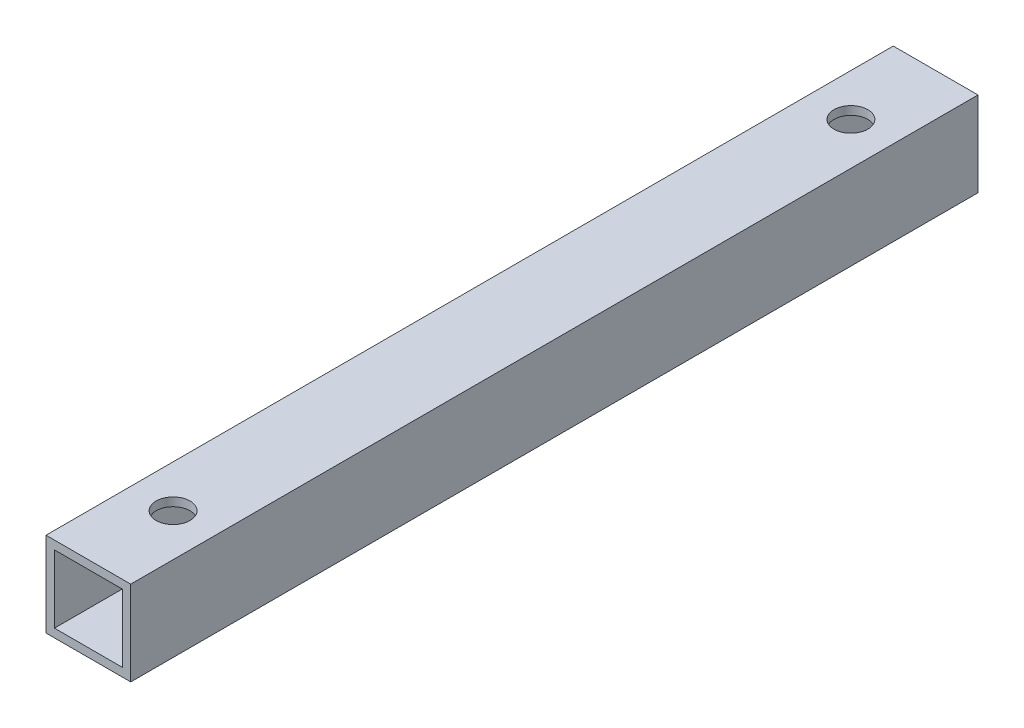
SolidWorks part; units mm, degrees
ref_plane "前视基准面" through (0, 0, 0) normal (0, 0, 1) x (1, 0, 0)
ref_plane "上视基准面" through (0, 0, 0) normal (0, 1, 0) x (1, 0, 0)
ref_plane "右视基准面" through (0, 0, 0) normal (1, 0, 0) x (0, 0, -1)
sketch "草图1" plane through (0, 0, 0) normal (0, 0, 1) x (1, 0, 0)
  line L0 (0, 0) -> (0, 8)
  line L1 (0, 8) -> (8, 8)
  line L2 (8, 8) -> (8, 0)
  line L3 (8, 0) -> (0, 0)
  line L4 (-1, 5.8968) -> (-1, 9)
  line L5 (-1, 9) -> (9, 9)
  line L6 (9, 9) -> (9, -1)
  line L7 (9, -1) -> (-1, -1)
  line L8 (-1, -1) -> (-1, 5.8968)
  dimension "D1" = 8
  dimension "D2" = 8
  dimension "D3" = 10
  dimension "D4" = 1
  dimension "D5" = 1
  dimension "D6" = 1
  dimension "D7" = 1
extrude "凸台-拉伸1" add sketch "草图1" along normal blind 100
sketch "草图2" plane through (0, 9, 0) normal (0, 1, 0) x (1, 0, 0)
  line L0 (9, -100) -> (9, 0) construction
  line L1 (9, -100) -> (-1, -100) construction
  line L2 (9, 0) -> (-1, 0) construction
  circle A0 centre (4, -90) radius 2
  circle A1 centre (4, -10) radius 2
  dimension "D1" = 5
  dimension "D2" = 10
  dimension "D3" = 10
extrude "切除-拉伸1" cut sketch "草图2" against normal blind 104
